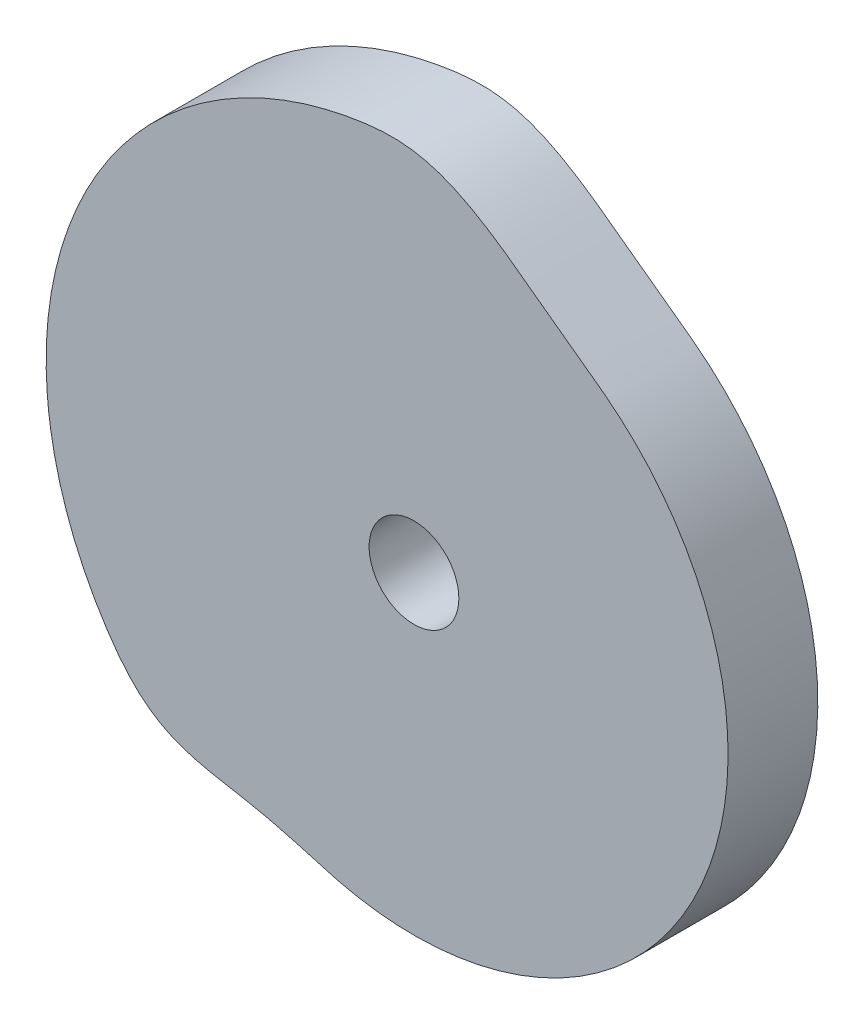
SolidWorks part; units mm, degrees
ref_plane "前视基准面" through (0, 0, 0) normal (0, 0, 1) x (1, 0, 0)
ref_plane "上视基准面" through (0, 0, 0) normal (0, 1, 0) x (1, 0, 0)
ref_plane "右视基准面" through (0, 0, 0) normal (1, 0, 0) x (0, 0, -1)
other "Configuration Table"
curve "曲线2"
sketch "草图2" plane through (0, 0, 0) normal (0, 0, 1) x (1, 0, 0)
  circle A0 centre (0, 0) radius 10
  spline S0 degree 3 poles (-81.0942, -12.06) (-80.9857, -12.7672) (-80.8712, -13.4734) (-80.7506, -14.1787) (-80.6238, -14.8828) (-80.4908, -15.5858) (-80.3518, -16.2876) (-80.2066, -16.9882) (-80.0553, -17.6875) (-79.8979, -18.3854) (-79.7344, -19.0819) (-79.5648, -19.777) (-79.3892, -20.4705) (-79.2076, -21.1626) (-79.0199, -21.853) (-78.8262, -22.5417) (-78.6265, -23.2288) (-78.4208, -23.914) (-78.2091, -24.5974) (-77.9915, -25.279) (-77.7679, -25.9586) (-77.5384, -26.6363) (-77.303, -27.3119) (-77.0616, -27.9854) (-76.8146, -28.6569) (-76.5615, -29.3261) (-76.3028, -29.9931) (-76.038, -30.6578) (-75.7677, -31.3202) (-75.4915, -31.9802) (-75.2095, -32.6378) (-74.9219, -33.2928) (-74.6284, -33.9454) (-74.3294, -34.5953) (-74.0246, -35.2426) (-73.7143, -35.8873) (-73.3983, -36.5292) (-73.0767, -37.1683) (-72.7496, -37.8046) (-72.4169, -38.438) (-72.0787, -39.0685) (-71.7351, -39.6961) (-71.3859, -40.3205) (-71.0314, -40.942) (-70.6714, -41.5602) (-70.306, -42.1753) (-69.9353, -42.7873) (-69.5592, -43.3959) (-69.1779, -44.0013) (-68.7913, -44.6033) (-68.3996, -45.2017) (-68.0035, -45.7953) (-67.6048, -46.382) (-67.2043, -46.9592) (-66.8026, -47.5253) (-66.3997, -48.08) (-65.9953, -48.623) (-65.5891, -49.1539) (-65.1809, -49.6725) (-64.7706, -50.1789) (-64.3578, -50.6725) (-63.9426, -51.1536) (-63.5246, -51.6219) (-63.1038, -52.0775) (-62.6799, -52.5204) (-62.2527, -52.9504) (-61.8221, -53.3679) (-61.388, -53.7728) (-60.9501, -54.1651) (-60.5083, -54.5453) (-60.0623, -54.9133) (-59.6122, -55.2696) (-59.1575, -55.6139) (-58.698, -55.9466) (-58.2338, -56.2682) (-57.7645, -56.5786) (-57.2899, -56.8781) (-56.8099, -57.1669) (-56.3243, -57.4454) (-55.8328, -57.7136) (-55.3355, -57.9718) (-54.8321, -58.2204) (-54.3224, -58.4593) (-53.8063, -58.6891) (-53.2838, -58.9098) (-52.7547, -59.1217) (-52.219, -59.3251) (-51.6766, -59.5202) (-51.1274, -59.7075) (-50.5714, -59.8872) (-50.0085, -60.0595) (-49.4387, -60.2249) (-48.8621, -60.3839) (-48.2785, -60.5366) (-47.6879, -60.6836) (-47.0904, -60.8254) (-46.486, -60.9624) (-45.8747, -61.0951) (-45.2566, -61.2241) (-44.6316, -61.35) (-43.9999, -61.473) (-43.3615, -61.5941) (-42.7165, -61.7137) (-42.0651, -61.8325) (-41.4075, -61.9509) (-40.7439, -62.0698) (-40.0745, -62.1898) (-39.3997, -62.311) (-38.7199, -62.4346) (-38.0353, -62.5605) (-37.3464, -62.6896) (-36.6537, -62.8222) (-35.9578, -62.9587) (-35.2593, -63.0995) (-34.5586, -63.2444) (-33.8564, -63.3942) (-33.1533, -63.5487) (-32.4498, -63.7077) (-31.7467, -63.8715) (-31.0444, -64.0397) (-30.3436, -64.2123) (-29.6448, -64.3889) (-28.9484, -64.5692) (-28.2548, -64.7528) (-27.5646, -64.9393) (-26.8781, -65.1283) (-26.1956, -65.3189) (-25.5174, -65.5111) (-24.8438, -65.7039) (-24.1749, -65.897) (-23.5111, -66.0896) (-22.8525, -66.2812) (-22.1992, -66.471) (-21.5516, -66.6588) (-20.9096, -66.8433) (-20.2735, -67.0247) (-19.6435, -67.2017) (-19.0197, -67.3742) (-18.4023, -67.5415) (-17.7915, -67.7029) (-17.1873, -67.8582) (-16.5885, -68.0069) (-15.9926, -68.1497) (-15.397, -68.2865) (-14.8005, -68.4184) (-14.2029, -68.5448) (-13.6042, -68.6663) (-13.0044, -68.7824) (-12.4037, -68.8932) (-11.802, -68.9988) (-11.1995, -69.0992) (-10.596, -69.1943) (-9.9918, -69.2841) (-9.3868, -69.3687) (-8.7811, -69.448) (-8.1747, -69.5218) (-7.5677, -69.5906) (-6.9602, -69.654) (-6.3521, -69.7121) (-5.7435, -69.7649) (-5.1345, -69.8122) (-4.525, -69.8545) (-3.9153, -69.8913) (-3.3052, -69.9228) (-2.6949, -69.949) (-2.0844, -69.9699) (-1.4737, -69.9854) (-0.8629, -69.9956) (-0.2521, -70.0003) (0.3588, -70) (0.9696, -69.9942) (1.5804, -69.9831) (2.191, -69.9666) (2.8015, -69.9448) (3.4118, -69.9177) (4.0219, -69.8853) (4.6315, -69.8475) (5.2409, -69.8044) (5.8499, -69.756) (6.4584, -69.7023) (7.0664, -69.6433) (7.6738, -69.579) (8.2807, -69.5094) (8.887, -69.4345) (9.4926, -69.3543) (10.0974, -69.2687) (10.7016, -69.1781) (11.3048, -69.0819) (11.9073, -68.9808) (12.5087, -68.8741) (13.1093, -68.7625) (13.7088, -68.6453) (14.3074, -68.5232) (14.9048, -68.3956) (15.5011, -68.2631) (16.0962, -68.1252) (16.69, -67.982) (17.2827, -67.8339) (17.874, -67.6804) (18.4639, -67.522) (19.0525, -67.3583) (19.6395, -67.1893) (20.2251, -67.0154) (20.8092, -66.8365) (21.3916, -66.6522) (21.9724, -66.463) (22.5516, -66.2687) (23.129, -66.0694) (23.7047, -65.8652) (24.2786, -65.6557) (24.8506, -65.4413) (25.4207, -65.222) (25.9889, -64.9977) (26.5551, -64.7684) (27.1193, -64.5342) (27.6815, -64.2951) (28.2415, -64.0511) (28.7993, -63.8022) (29.355, -63.5485) (29.9085, -63.2899) (30.4596, -63.0265) (31.0085, -62.7583) (31.5549, -62.4853) (32.099, -62.2075) (32.6407, -61.9251) (33.1798, -61.6379) (33.7164, -61.346) (34.2504, -61.0493) (34.7819, -60.7482) (35.3108, -60.4424) (35.8368, -60.1319) (36.3602, -59.8168) (36.8808, -59.4974) (37.3986, -59.1732) (37.9135, -58.8446) (38.4256, -58.5115) (38.9348, -58.174) (39.4409, -57.8319) (39.9441, -57.4855) (40.4442, -57.1348) (40.9413, -56.7798) (41.4352, -56.4202) (41.926, -56.0566) (42.4135, -55.6885) (42.898, -55.3163) (43.379, -54.9398) (43.8569, -54.5592) (44.3313, -54.1744) (44.8023, -53.7854) (45.27, -53.3925) (45.7342, -52.9954) (46.1949, -52.5943) (46.6521, -52.1891) (47.1058, -51.7801) (47.5558, -51.3669) (48.0023, -50.9501) (48.4451, -50.5293) (48.8841, -50.1045) (49.3195, -49.6761) (49.7511, -49.2437) (50.1791, -48.8077) (50.603, -48.3679) (51.0232, -47.9245) (51.4394, -47.4774) (51.8518, -47.0268) (52.2601, -46.5725) (52.6647, -46.1147) (53.065, -45.6533) (53.4614, -45.1885) (53.8537, -44.7203) (54.2419, -44.2486) (54.626, -43.7736) (55.0059, -43.2952) (55.3816, -42.8135) (55.7531, -42.3286) (56.1204, -41.8404) (56.4834, -41.3492) (56.842, -40.8547) (57.1964, -40.3571) (57.5464, -39.8564) (57.892, -39.3527) (58.2332, -38.846) (58.5701, -38.3364) (58.9023, -37.8238) (59.2302, -37.3084) (59.5534, -36.7901) (59.8723, -36.269) (60.1864, -35.745) (60.4962, -35.2186) (60.8011, -34.6892) (61.1016, -34.1574) (61.3972, -33.6228) (61.6884, -33.0858) (61.9748, -32.5462) (62.2564, -32.0041) (62.5333, -31.4596) (62.8055, -30.9127) (63.0728, -30.3634) (63.3354, -29.8119) (63.5931, -29.2581) (63.846, -28.702) (64.0941, -28.1438) (64.3372, -27.5833) (64.5755, -27.0209) (64.8088, -26.4563) (65.0372, -25.8897) (65.2607, -25.3212) (65.4793, -24.7508) (65.6926, -24.1784) (65.9011, -23.6042) (66.1047, -23.0283) (66.303, -22.4505) (66.4964, -21.8711) (66.6849, -21.29) (66.868, -20.7072) (67.0463, -20.1229) (67.2192, -19.537) (67.3872, -18.9497) (67.5499, -18.3609) (67.7077, -17.7707) (67.8602, -17.1792) (68.0074, -16.5864) (68.1497, -15.9923) (68.2865, -15.397) (68.4184, -14.8005) (68.5448, -14.2029) (68.6663, -13.6042) (68.7824, -13.0044) (68.8932, -12.4037) (68.9988, -11.802) (69.0992, -11.1995) (69.1943, -10.596) (69.2841, -9.9918) (69.3687, -9.3868) (69.448, -8.7811) (69.5218, -8.1747) (69.5906, -7.5677) (69.654, -6.9602) (69.7121, -6.3521) (69.7649, -5.7435) (69.8122, -5.1345) (69.8545, -4.525) (69.8913, -3.9153) (69.9228, -3.3052) (69.949, -2.6949) (69.9699, -2.0844) (69.9854, -1.4737) (69.9956, -0.8629) (70.0003, -0.2521) (70, 0.3588) (69.9942, 0.9696) (69.9831, 1.5804) (69.9666, 2.191) (69.9448, 2.8015) (69.9177, 3.4118) (69.8853, 4.0219) (69.8475, 4.6315) (69.8044, 5.2409) (69.756, 5.8499) (69.7023, 6.4584) (69.6433, 7.0664) (69.579, 7.6738) (69.5094, 8.2807) (69.4345, 8.887) (69.3543, 9.4926) (69.2687, 10.0974) (69.1781, 10.7016) (69.0819, 11.3048) (68.9808, 11.9073) (68.8741, 12.5087) (68.7625, 13.1093) (68.6453, 13.7088) (68.5232, 14.3074) (68.3956, 14.9048) (68.2631, 15.5011) (68.1252, 16.0962) (67.982, 16.69) (67.8339, 17.2827) (67.6804, 17.874) (67.522, 18.4639) (67.3583, 19.0525) (67.1893, 19.6395) (67.0154, 20.2251) (66.8365, 20.8092) (66.6522, 21.3916) (66.463, 21.9724) (66.2687, 22.5516) (66.0694, 23.129) (65.8652, 23.7047) (65.6557, 24.2786) (65.4413, 24.8506) (65.222, 25.4207) (64.9977, 25.9889) (64.7684, 26.5551) (64.5342, 27.1193) (64.2951, 27.6815) (64.0511, 28.2415) (63.8022, 28.7993) (63.5485, 29.355) (63.2899, 29.9085) (63.0265, 30.4596) (62.7583, 31.0085) (62.4853, 31.5549) (62.2075, 32.099) (61.9251, 32.6407) (61.6379, 33.1798) (61.346, 33.7164) (61.0493, 34.2504) (60.7482, 34.7819) (60.4424, 35.3108) (60.1319, 35.8368) (59.8168, 36.3602) (59.4974, 36.8808) (59.1732, 37.3986) (58.8446, 37.9135) (58.5115, 38.4256) (58.174, 38.9348) (57.8319, 39.4409) (57.4855, 39.9441) (57.1348, 40.4442) (56.7798, 40.9413) (56.4202, 41.4352) (56.0566, 41.926) (55.6885, 42.4135) (55.3163, 42.898) (54.9398, 43.379) (54.5592, 43.8569) (54.1744, 44.3313) (53.7854, 44.8023) (53.3925, 45.27) (52.9954, 45.7342) (52.5943, 46.1949) (52.1891, 46.6521) (51.7801, 47.1058) (51.3669, 47.5558) (50.9501, 48.0023) (50.5293, 48.4451) (50.1045, 48.8841) (49.6761, 49.3195) (49.2437, 49.7511) (48.8077, 50.1791) (48.3679, 50.603) (47.9245, 51.0232) (47.4774, 51.4394) (47.0268, 51.8518) (46.5725, 52.2601) (46.1147, 52.6647) (45.6533, 53.065) (45.1885, 53.4614) (44.7203, 53.8537) (44.2483, 54.242) (43.7719, 54.6274) (43.2884, 55.0112) (42.7963, 55.3958) (42.2945, 55.7823) (41.7829, 56.1713) (41.2618, 56.5633) (40.7315, 56.9585) (40.192, 57.3571) (39.644, 57.7596) (39.0877, 58.1662) (38.5235, 58.5771) (37.9517, 58.9923) (37.3728, 59.4123) (36.787, 59.8368) (36.195, 60.2663) (35.5969, 60.7003) (34.9934, 61.1394) (34.3845, 61.583) (33.7708, 62.0313) (33.1526, 62.4841) (32.5302, 62.9414) (31.9038, 63.4026) (31.2738, 63.8678) (30.6403, 64.3366) (30.0036, 64.8086) (29.3641, 65.2838) (28.7216, 65.7614) (28.0765, 66.2412) (27.4292, 66.7229) (26.7793, 67.2057) (26.1274, 67.6894) (25.4735, 68.1733) (24.8177, 68.657) (24.1602, 69.1398) (23.5012, 69.6213) (22.8407, 70.1008) (22.1791, 70.5776) (21.5163, 71.0511) (20.8526, 71.5207) (20.1884, 71.9857) (19.5235, 72.4455) (18.8584, 72.8994) (18.193, 73.3465) (17.5279, 73.7867) (16.863, 74.2187) (16.1988, 74.6424) (15.5353, 75.0568) (14.8728, 75.4615) (14.2117, 75.8561) (13.552, 76.2396) (12.894, 76.6119) (12.238, 76.9723) (11.584, 77.3205) (10.9323, 77.656) (10.2831, 77.9787) (9.6364, 78.2881) (8.9925, 78.584) (8.3512, 78.8662) (7.7128, 79.1346) (7.0771, 79.389) (6.4442, 79.6296) (5.814, 79.8561) (5.1863, 80.0686) (4.5609, 80.2672) (3.9378, 80.452) (3.3165, 80.6231) (2.6968, 80.7807) (2.0785, 80.9249) (1.461, 81.0557) (0.844, 81.1738) (0.2271, 81.2787) (-0.3902, 81.371) (-1.0083, 81.451) (-1.6277, 81.5184) (-2.2489, 81.5739) (-2.8723, 81.6175) (-3.4984, 81.6493) (-4.1278, 81.6696) (-4.7607, 81.6784) (-5.3977, 81.6761) (-6.0392, 81.6629) (-6.6855, 81.6391) (-7.337, 81.6045) (-7.994, 81.5598) (-8.6569, 81.5051) (-9.326, 81.4408) (-10.0014, 81.3669) (-10.6835, 81.2842) (-11.3724, 81.1926) (-12.068, 81.0929) (-12.7693, 80.9854) (-13.4737, 80.8712) (-14.1787, 80.7506) (-14.8828, 80.6238) (-15.5858, 80.4908) (-16.2876, 80.3518) (-16.9882, 80.2066) (-17.6875, 80.0553) (-18.3854, 79.8979) (-19.0819, 79.7344) (-19.777, 79.5648) (-20.4705, 79.3892) (-21.1626, 79.2076) (-21.853, 79.0199) (-22.5417, 78.8262) (-23.2288, 78.6265) (-23.914, 78.4208) (-24.5974, 78.2091) (-25.279, 77.9915) (-25.9586, 77.7679) (-26.6363, 77.5384) (-27.3119, 77.303) (-27.9854, 77.0616) (-28.6569, 76.8146) (-29.3261, 76.5615) (-29.9931, 76.3028) (-30.6578, 76.038) (-31.3202, 75.7677) (-31.9802, 75.4915) (-32.6378, 75.2095) (-33.2928, 74.9219) (-33.9454, 74.6284) (-34.5953, 74.3294) (-35.2426, 74.0246) (-35.8873, 73.7143) (-36.5292, 73.3983) (-37.1683, 73.0767) (-37.8046, 72.7496) (-38.438, 72.4169) (-39.0685, 72.0787) (-39.6961, 71.7351) (-40.3205, 71.3859) (-40.942, 71.0314) (-41.5602, 70.6714) (-42.1753, 70.306) (-42.7873, 69.9353) (-43.3959, 69.5592) (-44.0013, 69.1779) (-44.6033, 68.7913) (-45.2019, 68.3995) (-45.797, 68.0023) (-46.3888, 67.6002) (-46.9769, 67.1927) (-47.5615, 66.7803) (-48.1424, 66.3626) (-48.7198, 65.9401) (-49.2933, 65.5123) (-49.8632, 65.0797) (-50.4291, 64.642) (-50.9913, 64.1996) (-51.5496, 63.7521) (-52.104, 63.2998) (-52.6543, 62.8427) (-53.2008, 62.3809) (-53.743, 61.9141) (-54.2814, 61.4429) (-54.8155, 60.9669) (-55.3454, 60.4862) (-55.8711, 60.0008) (-56.3926, 59.5111) (-56.9098, 59.0167) (-57.4227, 58.5178) (-57.9311, 58.0145) (-58.4352, 57.5067) (-58.9348, 56.9946) (-59.4299, 56.4782) (-59.9205, 55.9574) (-60.4065, 55.4323) (-60.888, 54.9031) (-61.3648, 54.3697) (-61.8369, 53.8321) (-62.3043, 53.2904) (-62.767, 52.7447) (-63.2249, 52.195) (-63.6779, 51.6412) (-64.1261, 51.0835) (-64.5696, 50.5221) (-65.0079, 49.9566) (-65.4415, 49.3875) (-65.8698, 48.8144) (-66.2934, 48.2378) (-66.7117, 47.6574) (-67.1252, 47.0735) (-67.5333, 46.4859) (-67.9365, 45.8948) (-68.3343, 45.3002) (-68.7271, 44.7021) (-69.1146, 44.1007) (-69.4968, 43.4959) (-69.8737, 42.8877) (-70.2453, 42.2764) (-70.6115, 41.6618) (-70.9724, 41.044) (-71.3279, 40.4231) (-71.6779, 39.7991) (-72.0225, 39.1721) (-72.3616, 38.5421) (-72.6952, 37.9092) (-73.0232, 37.2733) (-73.3457, 36.6347) (-73.6626, 35.9932) (-73.974, 35.3491) (-74.2795, 34.7021) (-74.5796, 34.0526) (-74.8738, 33.4005) (-75.1626, 32.7459) (-75.4453, 32.0887) (-75.7226, 31.4291) (-75.994, 30.7671) (-76.2596, 30.1028) (-76.5194, 29.4362) (-76.7732, 28.7673) (-77.0214, 28.0962) (-77.2637, 27.4231) (-77.4999, 26.7477) (-77.7305, 26.0704) (-77.955, 25.3911) (-78.1736, 24.7098) (-78.3863, 24.0267) (-78.593, 23.3418) (-78.7937, 22.655) (-78.9884, 21.9666) (-79.1771, 21.2765) (-79.3597, 20.5847) (-79.5363, 19.8913) (-79.707, 19.1966) (-79.8713, 18.5002) (-80.0297, 17.8025) (-80.1822, 17.1035) (-80.3283, 16.4031) (-80.4683, 15.7015) (-80.6023, 14.9987) (-80.7301, 14.2947) (-80.8518, 13.5897) (-80.9674, 12.8836) (-81.0766, 12.1766) (-81.1799, 11.4686) (-81.2768, 10.7597) (-81.3676, 10.05) (-81.4522, 9.3396) (-81.5306, 8.6285) (-81.6028, 7.9167) (-81.6689, 7.2043) (-81.7285, 6.4913) (-81.7822, 5.7779) (-81.8295, 5.064) (-81.8704, 4.3497) (-81.9054, 3.635) (-81.934, 2.9201) (-81.9562, 2.205) (-81.9725, 1.4898) (-81.9822, 0.7744) (-81.986, 0.0589) (-81.9834, -0.6565) (-81.9744, -1.3719) (-81.9593, -2.0872) (-81.9381, -2.8023) (-81.9104, -3.5173) (-81.8766, -4.2319) (-81.8367, -4.9463) (-81.7903, -5.6602) (-81.7379, -6.3738) (-81.679, -7.0868) (-81.6142, -7.7993) (-81.5429, -8.5112) (-81.4655, -9.2225) (-81.3821, -9.9331) (-81.2922, -10.6428) (-81.1962, -11.3518) (-81.0942, -12.06) (-80.9857, -12.7672) (-80.8712, -13.4734) knots -0.004506 -0.003004 -0.001502 0 0.001502 0.003004 0.004506 0.006008 0.00751 0.009012 0.010514 0.012016 0.013518 0.015019 0.016521 0.018023 0.019525 0.021027 0.022529 0.024031 0.025533 0.027035 0.028537 0.030039 0.031541 0.033043 0.034544 0.036046 0.037548 0.03905 0.040552 0.042054 0.043556 0.045058 0.04656 0.048062 0.049564 0.051066 0.052568 0.05407 0.055571 0.057073 0.058575 0.060077 0.061579 0.063081 0.064583 0.066085 0.067587 0.069089 0.070591 0.072093 0.073595 0.075095 0.076587 0.078062 0.079519 0.080958 0.08238 0.083783 0.085168 0.086536 0.087887 0.089221 0.090538 0.09184 0.093127 0.094399 0.095658 0.096903 0.098137 0.09936 0.100574 0.101778 0.102975 0.104166 0.105351 0.106531 0.107709 0.108885 0.110059 0.111234 0.11241 0.113588 0.11477 0.115955 0.117146 0.118342 0.119544 0.120754 0.121972 0.123199 0.124434 0.125679 0.126935 0.128201 0.129479 0.130768 0.132068 0.133381 0.134707 0.136045 0.137396 0.13876 0.140138 0.141527 0.14293 0.144346 0.145773 0.147213 0.148664 0.150125 0.151597 0.153078 0.154567 0.156063 0.157565 0.159073 0.160584 0.162099 0.163615 0.165131 0.166647 0.16816 0.169671 0.171177 0.172679 0.174173 0.175662 0.177142 0.178613 0.180074 0.181526 0.182966 0.184394 0.18581 0.187213 0.188601 0.189975 0.191334 0.192677 0.194004 0.195313 0.196606 0.19789 0.199172 0.200454 0.201737 0.203019 0.204302 0.205584 0.206866 0.208149 0.209431 0.210713 0.211996 0.213278 0.214561 0.215843 0.217125 0.218408 0.21969 0.220972 0.222255 0.223537 0.224819 0.226102 0.227384 0.228667 0.229949 0.231231 0.232514 0.233796 0.235079 0.236361 0.237643 0.238926 0.240208 0.24149 0.242773 0.244055 0.245338 0.24662 0.247902 0.249185 0.250467 0.251749 0.253032 0.254314 0.255597 0.256879 0.258161 0.259444 0.260726 0.262008 0.263291 0.264573 0.265855 0.267138 0.26842 0.269702 0.270985 0.272267 0.27355 0.274832 0.276114 0.277397 0.278679 0.279962 0.281244 0.282526 0.283809 0.285091 0.286373 0.287656 0.288938 0.290221 0.291503 0.292785 0.294068 0.29535 0.296632 0.297915 0.299197 0.300479 0.301762 0.303044 0.304327 0.305609 0.306891 0.308174 0.309456 0.310739 0.312021 0.313303 0.314585 0.315868 0.31715 0.318433 0.319715 0.320997 0.32228 0.323562 0.324845 0.326127 0.327409 0.328692 0.329974 0.331256 0.332539 0.333821 0.335103 0.336386 0.337668 0.338951 0.340233 0.341515 0.342798 0.34408 0.345362 0.346645 0.347927 0.34921 0.350492 0.351774 0.353057 0.354339 0.355621 0.356904 0.358186 0.359469 0.360751 0.362033 0.363316 0.364598 0.36588 0.367163 0.368445 0.369728 0.37101 0.372292 0.373575 0.374857 0.376139 0.377422 0.378704 0.379986 0.381269 0.382551 0.383834 0.385116 0.386398 0.387681 0.388963 0.390245 0.391528 0.39281 0.394093 0.395375 0.396657 0.39794 0.399222 0.400504 0.401787 0.403069 0.404352 0.405634 0.406916 0.408199 0.409481 0.410763 0.412046 0.413328 0.414611 0.415893 0.417175 0.418458 0.41974 0.421022 0.422305 0.423587 0.42487 0.426152 0.427434 0.428717 0.429999 0.431281 0.432564 0.433846 0.435129 0.436411 0.437693 0.438976 0.440258 0.44154 0.442823 0.444105 0.445388 0.44667 0.447952 0.449235 0.450517 0.451799 0.453082 0.454364 0.455646 0.456929 0.458211 0.459494 0.460776 0.462058 0.463341 0.464623 0.465905 0.467188 0.46847 0.469753 0.471035 0.472317 0.4736 0.474882 0.476165 0.477447 0.478729 0.480012 0.481294 0.482576 0.483859 0.485141 0.486424 0.487706 0.488988 0.49027 0.491553 0.492835 0.494118 0.4954 0.496682 0.497965 0.499247 0.500529 0.501812 0.503094 0.504377 0.505659 0.506941 0.508224 0.509506 0.510789 0.512071 0.513353 0.514636 0.515918 0.5172 0.518483 0.519765 0.521048 0.52233 0.523612 0.524895 0.526177 0.527459 0.528742 0.530024 0.531306 0.532589 0.533871 0.535154 0.536436 0.537718 0.539001 0.540283 0.541565 0.542848 0.54413 0.545412 0.546695 0.547977 0.54926 0.550542 0.551824 0.553107 0.554389 0.555672 0.556954 0.558236 0.559519 0.560801 0.562083 0.563366 0.564648 0.56593 0.567213 0.568495 0.569778 0.57106 0.572342 0.573625 0.574907 0.576189 0.577472 0.578754 0.580037 0.581319 0.582601 0.583884 0.585166 0.586448 0.587731 0.589013 0.590296 0.591578 0.59286 0.594144 0.595437 0.596748 0.598077 0.599427 0.600795 0.602184 0.603592 0.605019 0.606466 0.607931 0.609415 0.610917 0.612436 0.613971 0.615523 0.61709 0.618671 0.620267 0.621876 0.623498 0.625131 0.626775 0.62843 0.630094 0.631767 0.633448 0.635136 0.63683 0.63853 0.640234 0.641942 0.643653 0.645366 0.64708 0.648793 0.650506 0.652216 0.653923 0.655626 0.657323 0.659014 0.660697 0.662372 0.664036 0.66569 0.667333 0.668963 0.67058 0.672182 0.673769 0.675341 0.676896 0.678435 0.679957 0.681461 0.682949 0.68442 0.685873 0.687311 0.688732 0.690137 0.691528 0.692905 0.694269 0.695621 0.696963 0.698295 0.69962 0.700938 0.702251 0.703561 0.704869 0.706176 0.707485 0.708796 0.710112 0.711433 0.712761 0.714098 0.715444 0.716802 0.718171 0.719553 0.720949 0.72236 0.723786 0.725228 0.726687 0.728162 0.729654 0.731155 0.732656 0.734158 0.73566 0.737162 0.738664 0.740166 0.741668 0.74317 0.744672 0.746174 0.747676 0.749178 0.75068 0.752182 0.753683 0.755185 0.756687 0.758189 0.759691 0.761193 0.762695 0.764197 0.765699 0.767201 0.768703 0.770205 0.771707 0.773208 0.77471 0.776212 0.777714 0.779216 0.780718 0.78222 0.783722 0.785224 0.786726 0.788228 0.78973 0.791232 0.792734 0.794236 0.795738 0.797239 0.798741 0.800243 0.801745 0.803247 0.804749 0.806251 0.807753 0.809255 0.810757 0.812259 0.813761 0.815263 0.816765 0.818267 0.819768 0.82127 0.822772 0.824274 0.825776 0.827278 0.82878 0.830282 0.831784 0.833286 0.834788 0.83629 0.837792 0.839293 0.840795 0.842297 0.843799 0.845301 0.846803 0.848305 0.849807 0.851309 0.852811 0.854313 0.855815 0.857317 0.858819 0.860321 0.861823 0.863324 0.864826 0.866328 0.86783 0.869332 0.870834 0.872336 0.873838 0.87534 0.876842 0.878344 0.879846 0.881347 0.882849 0.884351 0.885853 0.887355 0.888857 0.890359 0.891861 0.893363 0.894865 0.896367 0.897869 0.899371 0.900873 0.902375 0.903876 0.905378 0.90688 0.908382 0.909884 0.911386 0.912888 0.91439 0.915892 0.917394 0.918896 0.920398 0.9219 0.923402 0.924904 0.926406 0.927907 0.929409 0.930911 0.932413 0.933915 0.935417 0.936919 0.938421 0.939923 0.941425 0.942927 0.944429 0.945931 0.947433 0.948934 0.950436 0.951938 0.95344 0.954942 0.956444 0.957946 0.959448 0.96095 0.962452 0.963954 0.965456 0.966958 0.96846 0.969961 0.971463 0.972965 0.974467 0.975969 0.977471 0.978973 0.980475 0.981977 0.983479 0.984981 0.986483 0.987985 0.989486 0.990988 0.99249 0.993992 0.995494 0.996996 0.998498 1 1.001502 1.003004 1.004506 only from (-80.9847, -12.767) to (-80.9847, -12.767) construction
  spline S1 degree 3 poles (-81.0942, -12.06) (-80.9857, -12.7672) (-80.8712, -13.4734) (-80.7506, -14.1787) (-80.6238, -14.8828) (-80.4908, -15.5858) (-80.3518, -16.2876) (-80.2066, -16.9882) (-80.0553, -17.6875) (-79.8979, -18.3854) (-79.7344, -19.0819) (-79.5648, -19.777) (-79.3892, -20.4705) (-79.2076, -21.1626) (-79.0199, -21.853) (-78.8262, -22.5417) (-78.6265, -23.2288) (-78.4208, -23.914) (-78.2091, -24.5974) (-77.9915, -25.279) (-77.7679, -25.9586) (-77.5384, -26.6363) (-77.303, -27.3119) (-77.0616, -27.9854) (-76.8146, -28.6569) (-76.5615, -29.3261) (-76.3028, -29.9931) (-76.038, -30.6578) (-75.7677, -31.3202) (-75.4915, -31.9802) (-75.2095, -32.6378) (-74.9219, -33.2928) (-74.6284, -33.9454) (-74.3294, -34.5953) (-74.0246, -35.2426) (-73.7143, -35.8873) (-73.3983, -36.5292) (-73.0767, -37.1683) (-72.7496, -37.8046) (-72.4169, -38.438) (-72.0787, -39.0685) (-71.7351, -39.6961) (-71.3859, -40.3205) (-71.0314, -40.942) (-70.6714, -41.5602) (-70.306, -42.1753) (-69.9353, -42.7873) (-69.5592, -43.3959) (-69.1779, -44.0013) (-68.7913, -44.6033) (-68.3996, -45.2017) (-68.0035, -45.7953) (-67.6048, -46.382) (-67.2043, -46.9592) (-66.8026, -47.5253) (-66.3997, -48.08) (-65.9953, -48.623) (-65.5891, -49.1539) (-65.1809, -49.6725) (-64.7706, -50.1789) (-64.3578, -50.6725) (-63.9426, -51.1536) (-63.5246, -51.6219) (-63.1038, -52.0775) (-62.6799, -52.5204) (-62.2527, -52.9504) (-61.8221, -53.3679) (-61.388, -53.7728) (-60.9501, -54.1651) (-60.5083, -54.5453) (-60.0623, -54.9133) (-59.6122, -55.2696) (-59.1575, -55.6139) (-58.698, -55.9466) (-58.2338, -56.2682) (-57.7645, -56.5786) (-57.2899, -56.8781) (-56.8099, -57.1669) (-56.3243, -57.4454) (-55.8328, -57.7136) (-55.3355, -57.9718) (-54.8321, -58.2204) (-54.3224, -58.4593) (-53.8063, -58.6891) (-53.2838, -58.9098) (-52.7547, -59.1217) (-52.219, -59.3251) (-51.6766, -59.5202) (-51.1274, -59.7075) (-50.5714, -59.8872) (-50.0085, -60.0595) (-49.4387, -60.2249) (-48.8621, -60.3839) (-48.2785, -60.5366) (-47.6879, -60.6836) (-47.0904, -60.8254) (-46.486, -60.9624) (-45.8747, -61.0951) (-45.2566, -61.2241) (-44.6316, -61.35) (-43.9999, -61.473) (-43.3615, -61.5941) (-42.7165, -61.7137) (-42.0651, -61.8325) (-41.4075, -61.9509) (-40.7439, -62.0698) (-40.0745, -62.1898) (-39.3997, -62.311) (-38.7199, -62.4346) (-38.0353, -62.5605) (-37.3464, -62.6896) (-36.6537, -62.8222) (-35.9578, -62.9587) (-35.2593, -63.0995) (-34.5586, -63.2444) (-33.8564, -63.3942) (-33.1533, -63.5487) (-32.4498, -63.7077) (-31.7467, -63.8715) (-31.0444, -64.0397) (-30.3436, -64.2123) (-29.6448, -64.3889) (-28.9484, -64.5692) (-28.2548, -64.7528) (-27.5646, -64.9393) (-26.8781, -65.1283) (-26.1956, -65.3189) (-25.5174, -65.5111) (-24.8438, -65.7039) (-24.1749, -65.897) (-23.5111, -66.0896) (-22.8525, -66.2812) (-22.1992, -66.471) (-21.5516, -66.6588) (-20.9096, -66.8433) (-20.2735, -67.0247) (-19.6435, -67.2017) (-19.0197, -67.3742) (-18.4023, -67.5415) (-17.7915, -67.7029) (-17.1873, -67.8582) (-16.5885, -68.0069) (-15.9926, -68.1497) (-15.397, -68.2865) (-14.8005, -68.4184) (-14.2029, -68.5448) (-13.6042, -68.6663) (-13.0044, -68.7824) (-12.4037, -68.8932) (-11.802, -68.9988) (-11.1995, -69.0992) (-10.596, -69.1943) (-9.9918, -69.2841) (-9.3868, -69.3687) (-8.7811, -69.448) (-8.1747, -69.5218) (-7.5677, -69.5906) (-6.9602, -69.654) (-6.3521, -69.7121) (-5.7435, -69.7649) (-5.1345, -69.8122) (-4.525, -69.8545) (-3.9153, -69.8913) (-3.3052, -69.9228) (-2.6949, -69.949) (-2.0844, -69.9699) (-1.4737, -69.9854) (-0.8629, -69.9956) (-0.2521, -70.0003) (0.3588, -70) (0.9696, -69.9942) (1.5804, -69.9831) (2.191, -69.9666) (2.8015, -69.9448) (3.4118, -69.9177) (4.0219, -69.8853) (4.6315, -69.8475) (5.2409, -69.8044) (5.8499, -69.756) (6.4584, -69.7023) (7.0664, -69.6433) (7.6738, -69.579) (8.2807, -69.5094) (8.887, -69.4345) (9.4926, -69.3543) (10.0974, -69.2687) (10.7016, -69.1781) (11.3048, -69.0819) (11.9073, -68.9808) (12.5087, -68.8741) (13.1093, -68.7625) (13.7088, -68.6453) (14.3074, -68.5232) (14.9048, -68.3956) (15.5011, -68.2631) (16.0962, -68.1252) (16.69, -67.982) (17.2827, -67.8339) (17.874, -67.6804) (18.4639, -67.522) (19.0525, -67.3583) (19.6395, -67.1893) (20.2251, -67.0154) (20.8092, -66.8365) (21.3916, -66.6522) (21.9724, -66.463) (22.5516, -66.2687) (23.129, -66.0694) (23.7047, -65.8652) (24.2786, -65.6557) (24.8506, -65.4413) (25.4207, -65.222) (25.9889, -64.9977) (26.5551, -64.7684) (27.1193, -64.5342) (27.6815, -64.2951) (28.2415, -64.0511) (28.7993, -63.8022) (29.355, -63.5485) (29.9085, -63.2899) (30.4596, -63.0265) (31.0085, -62.7583) (31.5549, -62.4853) (32.099, -62.2075) (32.6407, -61.9251) (33.1798, -61.6379) (33.7164, -61.346) (34.2504, -61.0493) (34.7819, -60.7482) (35.3108, -60.4424) (35.8368, -60.1319) (36.3602, -59.8168) (36.8808, -59.4974) (37.3986, -59.1732) (37.9135, -58.8446) (38.4256, -58.5115) (38.9348, -58.174) (39.4409, -57.8319) (39.9441, -57.4855) (40.4442, -57.1348) (40.9413, -56.7798) (41.4352, -56.4202) (41.926, -56.0566) (42.4135, -55.6885) (42.898, -55.3163) (43.379, -54.9398) (43.8569, -54.5592) (44.3313, -54.1744) (44.8023, -53.7854) (45.27, -53.3925) (45.7342, -52.9954) (46.1949, -52.5943) (46.6521, -52.1891) (47.1058, -51.7801) (47.5558, -51.3669) (48.0023, -50.9501) (48.4451, -50.5293) (48.8841, -50.1045) (49.3195, -49.6761) (49.7511, -49.2437) (50.1791, -48.8077) (50.603, -48.3679) (51.0232, -47.9245) (51.4394, -47.4774) (51.8518, -47.0268) (52.2601, -46.5725) (52.6647, -46.1147) (53.065, -45.6533) (53.4614, -45.1885) (53.8537, -44.7203) (54.2419, -44.2486) (54.626, -43.7736) (55.0059, -43.2952) (55.3816, -42.8135) (55.7531, -42.3286) (56.1204, -41.8404) (56.4834, -41.3492) (56.842, -40.8547) (57.1964, -40.3571) (57.5464, -39.8564) (57.892, -39.3527) (58.2332, -38.846) (58.5701, -38.3364) (58.9023, -37.8238) (59.2302, -37.3084) (59.5534, -36.7901) (59.8723, -36.269) (60.1864, -35.745) (60.4962, -35.2186) (60.8011, -34.6892) (61.1016, -34.1574) (61.3972, -33.6228) (61.6884, -33.0858) (61.9748, -32.5462) (62.2564, -32.0041) (62.5333, -31.4596) (62.8055, -30.9127) (63.0728, -30.3634) (63.3354, -29.8119) (63.5931, -29.2581) (63.846, -28.702) (64.0941, -28.1438) (64.3372, -27.5833) (64.5755, -27.0209) (64.8088, -26.4563) (65.0372, -25.8897) (65.2607, -25.3212) (65.4793, -24.7508) (65.6926, -24.1784) (65.9011, -23.6042) (66.1047, -23.0283) (66.303, -22.4505) (66.4964, -21.8711) (66.6849, -21.29) (66.868, -20.7072) (67.0463, -20.1229) (67.2192, -19.537) (67.3872, -18.9497) (67.5499, -18.3609) (67.7077, -17.7707) (67.8602, -17.1792) (68.0074, -16.5864) (68.1497, -15.9923) (68.2865, -15.397) (68.4184, -14.8005) (68.5448, -14.2029) (68.6663, -13.6042) (68.7824, -13.0044) (68.8932, -12.4037) (68.9988, -11.802) (69.0992, -11.1995) (69.1943, -10.596) (69.2841, -9.9918) (69.3687, -9.3868) (69.448, -8.7811) (69.5218, -8.1747) (69.5906, -7.5677) (69.654, -6.9602) (69.7121, -6.3521) (69.7649, -5.7435) (69.8122, -5.1345) (69.8545, -4.525) (69.8913, -3.9153) (69.9228, -3.3052) (69.949, -2.6949) (69.9699, -2.0844) (69.9854, -1.4737) (69.9956, -0.8629) (70.0003, -0.2521) (70, 0.3588) (69.9942, 0.9696) (69.9831, 1.5804) (69.9666, 2.191) (69.9448, 2.8015) (69.9177, 3.4118) (69.8853, 4.0219) (69.8475, 4.6315) (69.8044, 5.2409) (69.756, 5.8499) (69.7023, 6.4584) (69.6433, 7.0664) (69.579, 7.6738) (69.5094, 8.2807) (69.4345, 8.887) (69.3543, 9.4926) (69.2687, 10.0974) (69.1781, 10.7016) (69.0819, 11.3048) (68.9808, 11.9073) (68.8741, 12.5087) (68.7625, 13.1093) (68.6453, 13.7088) (68.5232, 14.3074) (68.3956, 14.9048) (68.2631, 15.5011) (68.1252, 16.0962) (67.982, 16.69) (67.8339, 17.2827) (67.6804, 17.874) (67.522, 18.4639) (67.3583, 19.0525) (67.1893, 19.6395) (67.0154, 20.2251) (66.8365, 20.8092) (66.6522, 21.3916) (66.463, 21.9724) (66.2687, 22.5516) (66.0694, 23.129) (65.8652, 23.7047) (65.6557, 24.2786) (65.4413, 24.8506) (65.222, 25.4207) (64.9977, 25.9889) (64.7684, 26.5551) (64.5342, 27.1193) (64.2951, 27.6815) (64.0511, 28.2415) (63.8022, 28.7993) (63.5485, 29.355) (63.2899, 29.9085) (63.0265, 30.4596) (62.7583, 31.0085) (62.4853, 31.5549) (62.2075, 32.099) (61.9251, 32.6407) (61.6379, 33.1798) (61.346, 33.7164) (61.0493, 34.2504) (60.7482, 34.7819) (60.4424, 35.3108) (60.1319, 35.8368) (59.8168, 36.3602) (59.4974, 36.8808) (59.1732, 37.3986) (58.8446, 37.9135) (58.5115, 38.4256) (58.174, 38.9348) (57.8319, 39.4409) (57.4855, 39.9441) (57.1348, 40.4442) (56.7798, 40.9413) (56.4202, 41.4352) (56.0566, 41.926) (55.6885, 42.4135) (55.3163, 42.898) (54.9398, 43.379) (54.5592, 43.8569) (54.1744, 44.3313) (53.7854, 44.8023) (53.3925, 45.27) (52.9954, 45.7342) (52.5943, 46.1949) (52.1891, 46.6521) (51.7801, 47.1058) (51.3669, 47.5558) (50.9501, 48.0023) (50.5293, 48.4451) (50.1045, 48.8841) (49.6761, 49.3195) (49.2437, 49.7511) (48.8077, 50.1791) (48.3679, 50.603) (47.9245, 51.0232) (47.4774, 51.4394) (47.0268, 51.8518) (46.5725, 52.2601) (46.1147, 52.6647) (45.6533, 53.065) (45.1885, 53.4614) (44.7203, 53.8537) (44.2483, 54.242) (43.7719, 54.6274) (43.2884, 55.0112) (42.7963, 55.3958) (42.2945, 55.7823) (41.7829, 56.1713) (41.2618, 56.5633) (40.7315, 56.9585) (40.192, 57.3571) (39.644, 57.7596) (39.0877, 58.1662) (38.5235, 58.5771) (37.9517, 58.9923) (37.3728, 59.4123) (36.787, 59.8368) (36.195, 60.2663) (35.5969, 60.7003) (34.9934, 61.1394) (34.3845, 61.583) (33.7708, 62.0313) (33.1526, 62.4841) (32.5302, 62.9414) (31.9038, 63.4026) (31.2738, 63.8678) (30.6403, 64.3366) (30.0036, 64.8086) (29.3641, 65.2838) (28.7216, 65.7614) (28.0765, 66.2412) (27.4292, 66.7229) (26.7793, 67.2057) (26.1274, 67.6894) (25.4735, 68.1733) (24.8177, 68.657) (24.1602, 69.1398) (23.5012, 69.6213) (22.8407, 70.1008) (22.1791, 70.5776) (21.5163, 71.0511) (20.8526, 71.5207) (20.1884, 71.9857) (19.5235, 72.4455) (18.8584, 72.8994) (18.193, 73.3465) (17.5279, 73.7867) (16.863, 74.2187) (16.1988, 74.6424) (15.5353, 75.0568) (14.8728, 75.4615) (14.2117, 75.8561) (13.552, 76.2396) (12.894, 76.6119) (12.238, 76.9723) (11.584, 77.3205) (10.9323, 77.656) (10.2831, 77.9787) (9.6364, 78.2881) (8.9925, 78.584) (8.3512, 78.8662) (7.7128, 79.1346) (7.0771, 79.389) (6.4442, 79.6296) (5.814, 79.8561) (5.1863, 80.0686) (4.5609, 80.2672) (3.9378, 80.452) (3.3165, 80.6231) (2.6968, 80.7807) (2.0785, 80.9249) (1.461, 81.0557) (0.844, 81.1738) (0.2271, 81.2787) (-0.3902, 81.371) (-1.0083, 81.451) (-1.6277, 81.5184) (-2.2489, 81.5739) (-2.8723, 81.6175) (-3.4984, 81.6493) (-4.1278, 81.6696) (-4.7607, 81.6784) (-5.3977, 81.6761) (-6.0392, 81.6629) (-6.6855, 81.6391) (-7.337, 81.6045) (-7.994, 81.5598) (-8.6569, 81.5051) (-9.326, 81.4408) (-10.0014, 81.3669) (-10.6835, 81.2842) (-11.3724, 81.1926) (-12.068, 81.0929) (-12.7693, 80.9854) (-13.4737, 80.8712) (-14.1787, 80.7506) (-14.8828, 80.6238) (-15.5858, 80.4908) (-16.2876, 80.3518) (-16.9882, 80.2066) (-17.6875, 80.0553) (-18.3854, 79.8979) (-19.0819, 79.7344) (-19.777, 79.5648) (-20.4705, 79.3892) (-21.1626, 79.2076) (-21.853, 79.0199) (-22.5417, 78.8262) (-23.2288, 78.6265) (-23.914, 78.4208) (-24.5974, 78.2091) (-25.279, 77.9915) (-25.9586, 77.7679) (-26.6363, 77.5384) (-27.3119, 77.303) (-27.9854, 77.0616) (-28.6569, 76.8146) (-29.3261, 76.5615) (-29.9931, 76.3028) (-30.6578, 76.038) (-31.3202, 75.7677) (-31.9802, 75.4915) (-32.6378, 75.2095) (-33.2928, 74.9219) (-33.9454, 74.6284) (-34.5953, 74.3294) (-35.2426, 74.0246) (-35.8873, 73.7143) (-36.5292, 73.3983) (-37.1683, 73.0767) (-37.8046, 72.7496) (-38.438, 72.4169) (-39.0685, 72.0787) (-39.6961, 71.7351) (-40.3205, 71.3859) (-40.942, 71.0314) (-41.5602, 70.6714) (-42.1753, 70.306) (-42.7873, 69.9353) (-43.3959, 69.5592) (-44.0013, 69.1779) (-44.6033, 68.7913) (-45.2019, 68.3995) (-45.797, 68.0023) (-46.3888, 67.6002) (-46.9769, 67.1927) (-47.5615, 66.7803) (-48.1424, 66.3626) (-48.7198, 65.9401) (-49.2933, 65.5123) (-49.8632, 65.0797) (-50.4291, 64.642) (-50.9913, 64.1996) (-51.5496, 63.7521) (-52.104, 63.2998) (-52.6543, 62.8427) (-53.2008, 62.3809) (-53.743, 61.9141) (-54.2814, 61.4429) (-54.8155, 60.9669) (-55.3454, 60.4862) (-55.8711, 60.0008) (-56.3926, 59.5111) (-56.9098, 59.0167) (-57.4227, 58.5178) (-57.9311, 58.0145) (-58.4352, 57.5067) (-58.9348, 56.9946) (-59.4299, 56.4782) (-59.9205, 55.9574) (-60.4065, 55.4323) (-60.888, 54.9031) (-61.3648, 54.3697) (-61.8369, 53.8321) (-62.3043, 53.2904) (-62.767, 52.7447) (-63.2249, 52.195) (-63.6779, 51.6412) (-64.1261, 51.0835) (-64.5696, 50.5221) (-65.0079, 49.9566) (-65.4415, 49.3875) (-65.8698, 48.8144) (-66.2934, 48.2378) (-66.7117, 47.6574) (-67.1252, 47.0735) (-67.5333, 46.4859) (-67.9365, 45.8948) (-68.3343, 45.3002) (-68.7271, 44.7021) (-69.1146, 44.1007) (-69.4968, 43.4959) (-69.8737, 42.8877) (-70.2453, 42.2764) (-70.6115, 41.6618) (-70.9724, 41.044) (-71.3279, 40.4231) (-71.6779, 39.7991) (-72.0225, 39.1721) (-72.3616, 38.5421) (-72.6952, 37.9092) (-73.0232, 37.2733) (-73.3457, 36.6347) (-73.6626, 35.9932) (-73.974, 35.3491) (-74.2795, 34.7021) (-74.5796, 34.0526) (-74.8738, 33.4005) (-75.1626, 32.7459) (-75.4453, 32.0887) (-75.7226, 31.4291) (-75.994, 30.7671) (-76.2596, 30.1028) (-76.5194, 29.4362) (-76.7732, 28.7673) (-77.0214, 28.0962) (-77.2637, 27.4231) (-77.4999, 26.7477) (-77.7305, 26.0704) (-77.955, 25.3911) (-78.1736, 24.7098) (-78.3863, 24.0267) (-78.593, 23.3418) (-78.7937, 22.655) (-78.9884, 21.9666) (-79.1771, 21.2765) (-79.3597, 20.5847) (-79.5363, 19.8913) (-79.707, 19.1966) (-79.8713, 18.5002) (-80.0297, 17.8025) (-80.1822, 17.1035) (-80.3283, 16.4031) (-80.4683, 15.7015) (-80.6023, 14.9987) (-80.7301, 14.2947) (-80.8518, 13.5897) (-80.9674, 12.8836) (-81.0766, 12.1766) (-81.1799, 11.4686) (-81.2768, 10.7597) (-81.3676, 10.05) (-81.4522, 9.3396) (-81.5306, 8.6285) (-81.6028, 7.9167) (-81.6689, 7.2043) (-81.7285, 6.4913) (-81.7822, 5.7779) (-81.8295, 5.064) (-81.8704, 4.3497) (-81.9054, 3.635) (-81.934, 2.9201) (-81.9562, 2.205) (-81.9725, 1.4898) (-81.9822, 0.7744) (-81.986, 0.0589) (-81.9834, -0.6565) (-81.9744, -1.3719) (-81.9593, -2.0872) (-81.9381, -2.8023) (-81.9104, -3.5173) (-81.8766, -4.2319) (-81.8367, -4.9463) (-81.7903, -5.6602) (-81.7379, -6.3738) (-81.679, -7.0868) (-81.6142, -7.7993) (-81.5429, -8.5112) (-81.4655, -9.2225) (-81.3821, -9.9331) (-81.2922, -10.6428) (-81.1962, -11.3518) (-81.0942, -12.06) (-80.9857, -12.7672) (-80.8712, -13.4734) knots -0.004506 -0.003004 -0.001502 0 0.001502 0.003004 0.004506 0.006008 0.00751 0.009012 0.010514 0.012016 0.013518 0.015019 0.016521 0.018023 0.019525 0.021027 0.022529 0.024031 0.025533 0.027035 0.028537 0.030039 0.031541 0.033043 0.034544 0.036046 0.037548 0.03905 0.040552 0.042054 0.043556 0.045058 0.04656 0.048062 0.049564 0.051066 0.052568 0.05407 0.055571 0.057073 0.058575 0.060077 0.061579 0.063081 0.064583 0.066085 0.067587 0.069089 0.070591 0.072093 0.073595 0.075095 0.076587 0.078062 0.079519 0.080958 0.08238 0.083783 0.085168 0.086536 0.087887 0.089221 0.090538 0.09184 0.093127 0.094399 0.095658 0.096903 0.098137 0.09936 0.100574 0.101778 0.102975 0.104166 0.105351 0.106531 0.107709 0.108885 0.110059 0.111234 0.11241 0.113588 0.11477 0.115955 0.117146 0.118342 0.119544 0.120754 0.121972 0.123199 0.124434 0.125679 0.126935 0.128201 0.129479 0.130768 0.132068 0.133381 0.134707 0.136045 0.137396 0.13876 0.140138 0.141527 0.14293 0.144346 0.145773 0.147213 0.148664 0.150125 0.151597 0.153078 0.154567 0.156063 0.157565 0.159073 0.160584 0.162099 0.163615 0.165131 0.166647 0.16816 0.169671 0.171177 0.172679 0.174173 0.175662 0.177142 0.178613 0.180074 0.181526 0.182966 0.184394 0.18581 0.187213 0.188601 0.189975 0.191334 0.192677 0.194004 0.195313 0.196606 0.19789 0.199172 0.200454 0.201737 0.203019 0.204302 0.205584 0.206866 0.208149 0.209431 0.210713 0.211996 0.213278 0.214561 0.215843 0.217125 0.218408 0.21969 0.220972 0.222255 0.223537 0.224819 0.226102 0.227384 0.228667 0.229949 0.231231 0.232514 0.233796 0.235079 0.236361 0.237643 0.238926 0.240208 0.24149 0.242773 0.244055 0.245338 0.24662 0.247902 0.249185 0.250467 0.251749 0.253032 0.254314 0.255597 0.256879 0.258161 0.259444 0.260726 0.262008 0.263291 0.264573 0.265855 0.267138 0.26842 0.269702 0.270985 0.272267 0.27355 0.274832 0.276114 0.277397 0.278679 0.279962 0.281244 0.282526 0.283809 0.285091 0.286373 0.287656 0.288938 0.290221 0.291503 0.292785 0.294068 0.29535 0.296632 0.297915 0.299197 0.300479 0.301762 0.303044 0.304327 0.305609 0.306891 0.308174 0.309456 0.310739 0.312021 0.313303 0.314585 0.315868 0.31715 0.318433 0.319715 0.320997 0.32228 0.323562 0.324845 0.326127 0.327409 0.328692 0.329974 0.331256 0.332539 0.333821 0.335103 0.336386 0.337668 0.338951 0.340233 0.341515 0.342798 0.34408 0.345362 0.346645 0.347927 0.34921 0.350492 0.351774 0.353057 0.354339 0.355621 0.356904 0.358186 0.359469 0.360751 0.362033 0.363316 0.364598 0.36588 0.367163 0.368445 0.369728 0.37101 0.372292 0.373575 0.374857 0.376139 0.377422 0.378704 0.379986 0.381269 0.382551 0.383834 0.385116 0.386398 0.387681 0.388963 0.390245 0.391528 0.39281 0.394093 0.395375 0.396657 0.39794 0.399222 0.400504 0.401787 0.403069 0.404352 0.405634 0.406916 0.408199 0.409481 0.410763 0.412046 0.413328 0.414611 0.415893 0.417175 0.418458 0.41974 0.421022 0.422305 0.423587 0.42487 0.426152 0.427434 0.428717 0.429999 0.431281 0.432564 0.433846 0.435129 0.436411 0.437693 0.438976 0.440258 0.44154 0.442823 0.444105 0.445388 0.44667 0.447952 0.449235 0.450517 0.451799 0.453082 0.454364 0.455646 0.456929 0.458211 0.459494 0.460776 0.462058 0.463341 0.464623 0.465905 0.467188 0.46847 0.469753 0.471035 0.472317 0.4736 0.474882 0.476165 0.477447 0.478729 0.480012 0.481294 0.482576 0.483859 0.485141 0.486424 0.487706 0.488988 0.49027 0.491553 0.492835 0.494118 0.4954 0.496682 0.497965 0.499247 0.500529 0.501812 0.503094 0.504377 0.505659 0.506941 0.508224 0.509506 0.510789 0.512071 0.513353 0.514636 0.515918 0.5172 0.518483 0.519765 0.521048 0.52233 0.523612 0.524895 0.526177 0.527459 0.528742 0.530024 0.531306 0.532589 0.533871 0.535154 0.536436 0.537718 0.539001 0.540283 0.541565 0.542848 0.54413 0.545412 0.546695 0.547977 0.54926 0.550542 0.551824 0.553107 0.554389 0.555672 0.556954 0.558236 0.559519 0.560801 0.562083 0.563366 0.564648 0.56593 0.567213 0.568495 0.569778 0.57106 0.572342 0.573625 0.574907 0.576189 0.577472 0.578754 0.580037 0.581319 0.582601 0.583884 0.585166 0.586448 0.587731 0.589013 0.590296 0.591578 0.59286 0.594144 0.595437 0.596748 0.598077 0.599427 0.600795 0.602184 0.603592 0.605019 0.606466 0.607931 0.609415 0.610917 0.612436 0.613971 0.615523 0.61709 0.618671 0.620267 0.621876 0.623498 0.625131 0.626775 0.62843 0.630094 0.631767 0.633448 0.635136 0.63683 0.63853 0.640234 0.641942 0.643653 0.645366 0.64708 0.648793 0.650506 0.652216 0.653923 0.655626 0.657323 0.659014 0.660697 0.662372 0.664036 0.66569 0.667333 0.668963 0.67058 0.672182 0.673769 0.675341 0.676896 0.678435 0.679957 0.681461 0.682949 0.68442 0.685873 0.687311 0.688732 0.690137 0.691528 0.692905 0.694269 0.695621 0.696963 0.698295 0.69962 0.700938 0.702251 0.703561 0.704869 0.706176 0.707485 0.708796 0.710112 0.711433 0.712761 0.714098 0.715444 0.716802 0.718171 0.719553 0.720949 0.72236 0.723786 0.725228 0.726687 0.728162 0.729654 0.731155 0.732656 0.734158 0.73566 0.737162 0.738664 0.740166 0.741668 0.74317 0.744672 0.746174 0.747676 0.749178 0.75068 0.752182 0.753683 0.755185 0.756687 0.758189 0.759691 0.761193 0.762695 0.764197 0.765699 0.767201 0.768703 0.770205 0.771707 0.773208 0.77471 0.776212 0.777714 0.779216 0.780718 0.78222 0.783722 0.785224 0.786726 0.788228 0.78973 0.791232 0.792734 0.794236 0.795738 0.797239 0.798741 0.800243 0.801745 0.803247 0.804749 0.806251 0.807753 0.809255 0.810757 0.812259 0.813761 0.815263 0.816765 0.818267 0.819768 0.82127 0.822772 0.824274 0.825776 0.827278 0.82878 0.830282 0.831784 0.833286 0.834788 0.83629 0.837792 0.839293 0.840795 0.842297 0.843799 0.845301 0.846803 0.848305 0.849807 0.851309 0.852811 0.854313 0.855815 0.857317 0.858819 0.860321 0.861823 0.863324 0.864826 0.866328 0.86783 0.869332 0.870834 0.872336 0.873838 0.87534 0.876842 0.878344 0.879846 0.881347 0.882849 0.884351 0.885853 0.887355 0.888857 0.890359 0.891861 0.893363 0.894865 0.896367 0.897869 0.899371 0.900873 0.902375 0.903876 0.905378 0.90688 0.908382 0.909884 0.911386 0.912888 0.91439 0.915892 0.917394 0.918896 0.920398 0.9219 0.923402 0.924904 0.926406 0.927907 0.929409 0.930911 0.932413 0.933915 0.935417 0.936919 0.938421 0.939923 0.941425 0.942927 0.944429 0.945931 0.947433 0.948934 0.950436 0.951938 0.95344 0.954942 0.956444 0.957946 0.959448 0.96095 0.962452 0.963954 0.965456 0.966958 0.96846 0.969961 0.971463 0.972965 0.974467 0.975969 0.977471 0.978973 0.980475 0.981977 0.983479 0.984981 0.986483 0.987985 0.989486 0.990988 0.99249 0.993992 0.995494 0.996996 0.998498 1 1.001502 1.003004 1.004506 only from (-80.9847, -12.767) to (-80.9847, -12.767)
extrude "凸台-拉伸2" add sketch "草图2" along normal blind 20
